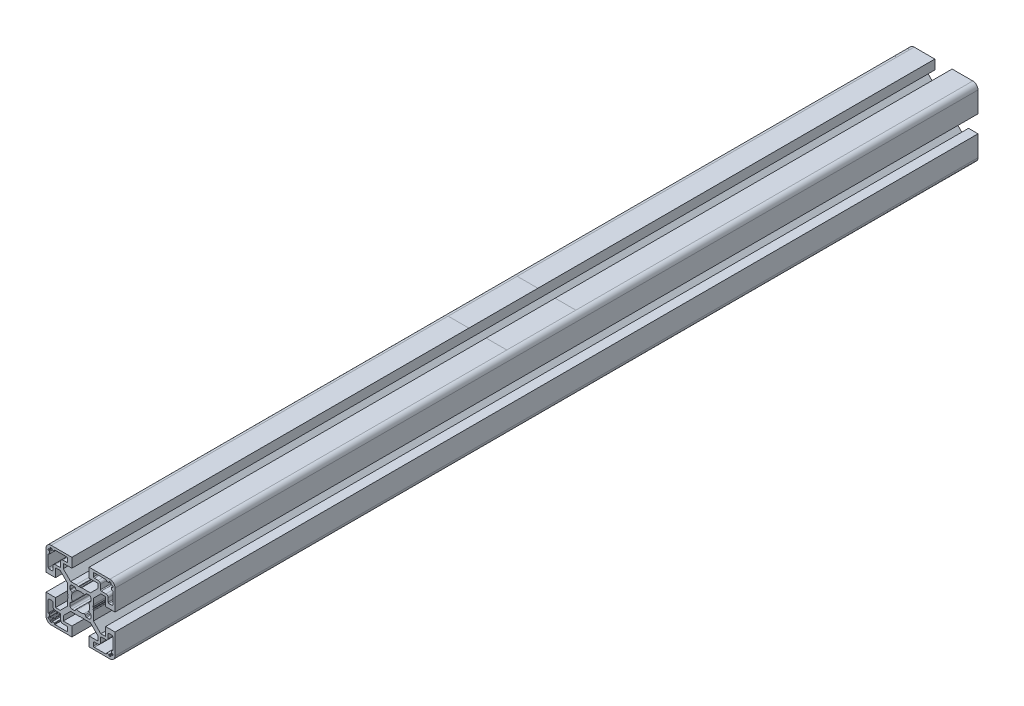
SolidWorks part; units mm, degrees
material "6063-T5"
ref_plane "Front Plane" through (0, 0, 0) normal (0, 0, 1) x (1, 0, 0)
ref_plane "Top Plane" through (0, 0, 0) normal (0, 1, 0) x (1, 0, 0)
ref_plane "Right Plane" through (0, 0, 0) normal (1, 0, 0) x (0, 0, -1)
ref_plane "Plan1" through (0, 0, 50) normal (0, 0, 1) x (1, 0, 0)
sketch "Esquisse1" plane through (0, 0, 50) normal (0, 0, 1) x (1, 0, 0)
  line L0 (-11.2645, -4.6769) -> (-11.2645, 2.1231)
  line L1 (-10.7645, 2.6231) -> (-9.0645, 2.6231)
  line L2 (-8.5645, 2.1231) -> (-8.5645, -0.0769)
  line L3 (-7.2645, -1.3769) -> (-4.5645, -1.3769)
  line L4 (-4.0645, -1.8769) -> (-4.0645, -4.5769)
  line L5 (-2.7645, -5.8769) -> (-0.5645, -5.8769)
  line L6 (-0.0645, -6.3769) -> (-0.0645, -8.0769)
  line L7 (-0.5645, -8.5769) -> (-7.3645, -8.5769)
  line L8 (-7.5645, -8.3769) -> (-7.5645, -8.0769)
  line L9 (-7.7645, -7.8769) -> (-8.9645, -7.8769)
  line L10 (-9.1645, -8.0769) -> (-9.1645, -8.3769)
  line L11 (-9.3645, -8.5769) -> (-9.8645, -8.5769)
  line L12 (-10.1645, -8.2769) -> (-10.1645, -7.7769)
  line L13 (-10.4645, -7.4769) -> (-10.9645, -7.4769)
  line L14 (-11.2645, -7.1769) -> (-11.2645, -6.6769)
  line L15 (-11.0645, -6.4769) -> (-10.7645, -6.4769)
  line L16 (-10.5645, -6.2769) -> (-10.5645, -5.0769)
  line L17 (-10.7645, -4.8769) -> (-11.0645, -4.8769)
  line L18 (14.9355, -8.0769) -> (14.9355, -6.3769)
  line L19 (15.4355, -5.8769) -> (17.6355, -5.8769)
  line L20 (18.9355, -4.5769) -> (18.9355, -1.8769)
  line L21 (19.4355, -1.3769) -> (22.1355, -1.3769)
  line L22 (23.4355, -0.0769) -> (23.4355, 2.1231)
  line L23 (23.9355, 2.6231) -> (25.6355, 2.6231)
  line L24 (26.1355, 2.1231) -> (26.1355, -4.6769)
  line L25 (25.9355, -4.8769) -> (25.6355, -4.8769)
  line L26 (25.4355, -5.0769) -> (25.4355, -6.2769)
  line L27 (25.6355, -6.4769) -> (25.9355, -6.4769)
  line L28 (26.1355, -6.6769) -> (26.1355, -7.1769)
  line L29 (25.8355, -7.4769) -> (25.3355, -7.4769)
  line L30 (25.0355, -7.7769) -> (25.0355, -8.2769)
  line L31 (24.7355, -8.5769) -> (24.2355, -8.5769)
  line L32 (24.0355, -8.3769) -> (24.0355, -8.0769)
  line L33 (23.8355, -7.8769) -> (22.6355, -7.8769)
  line L34 (22.4355, -8.0769) -> (22.4355, -8.3769)
  line L35 (22.2355, -8.5769) -> (15.4355, -8.5769)
  line L36 (-12.5645, 27.1231) -> (-12.5645, 15.1231)
  line L37 (-12.5645, 15.1231) -> (-7.0645, 15.1231)
  line L38 (-7.0645, 15.1231) -> (-7.0645, 20.1231)
  line L39 (-7.0645, 20.1231) -> (-4.3322, 20.1231)
  line L40 (-4.3322, 20.1231) -> (-0.0645, 15.8553)
  line L41 (-0.0645, 15.8553) -> (-0.0645, 10.7767)
  line L42 (0.0025, 10.5267) -> (0.2355, 10.1231)
  line L43 (0.2355, 10.1231) -> (0.0025, 9.7195)
  line L44 (0.0025, 9.2195) -> (0.1846, 8.9042)
  line L45 (0.1846, 8.9042) -> (-0.0645, 7.6231)
  line L46 (-0.0645, 7.6231) -> (-0.0645, 4.3908)
  line L47 (-0.0645, 4.3908) -> (-4.3322, 0.1231)
  line L48 (-4.3322, 0.1231) -> (-7.0645, 0.1231)
  line L49 (-7.0645, 0.1231) -> (-7.0645, 5.1231)
  line L50 (-7.0645, 5.1231) -> (-12.5645, 5.1231)
  line L51 (-12.5645, 5.1231) -> (-12.5645, -6.8769)
  line L52 (-9.5645, -9.8769) -> (2.4355, -9.8769)
  line L53 (2.4355, -9.8769) -> (2.4355, -4.3769)
  line L54 (2.4355, -4.3769) -> (-2.5645, -4.3769)
  line L55 (-2.5645, -4.3769) -> (-2.5645, -1.6447)
  line L56 (-2.5645, -1.6447) -> (1.7033, 2.6231)
  line L57 (1.7033, 2.6231) -> (6.7819, 2.6231)
  line L58 (7.0319, 2.6901) -> (7.4355, 2.9231)
  line L59 (7.4355, 2.9231) -> (7.8391, 2.6901)
  line L60 (8.3391, 2.6901) -> (8.6544, 2.8721)
  line L61 (8.6544, 2.8721) -> (9.9355, 2.6231)
  line L62 (9.9355, 2.6231) -> (13.1678, 2.6231)
  line L63 (13.1678, 2.6231) -> (17.4355, -1.6447)
  line L64 (17.4355, -1.6447) -> (17.4355, -4.3769)
  line L65 (17.4355, -4.3769) -> (12.4355, -4.3769)
  line L66 (12.4355, -4.3769) -> (12.4355, -9.8769)
  line L67 (12.4355, -9.8769) -> (24.4355, -9.8769)
  line L68 (27.4355, -6.8769) -> (27.4355, 5.1231)
  line L69 (27.4355, 5.1231) -> (21.9355, 5.1231)
  line L70 (21.9355, 5.1231) -> (21.9355, 0.1231)
  line L71 (21.9355, 0.1231) -> (19.2033, 0.1231)
  line L72 (19.2033, 0.1231) -> (14.9355, 4.3908)
  line L73 (14.9355, 4.3908) -> (14.9355, 9.4695)
  line L74 (14.8686, 9.7195) -> (14.6355, 10.1231)
  line L75 (14.6355, 10.1231) -> (14.8686, 10.5267)
  line L76 (14.8686, 11.0267) -> (14.6865, 11.342)
  line L77 (14.6865, 11.342) -> (14.9355, 12.6231)
  line L78 (14.9355, 12.6231) -> (14.9355, 15.8553)
  line L79 (14.9355, 15.8553) -> (19.2033, 20.1231)
  line L80 (19.2033, 20.1231) -> (21.9355, 20.1231)
  line L81 (21.9355, 20.1231) -> (21.9355, 15.1231)
  line L82 (21.9355, 15.1231) -> (27.4355, 15.1231)
  line L83 (27.4355, 15.1231) -> (27.4355, 27.1231)
  line L84 (24.4355, 30.1231) -> (12.4355, 30.1231)
  line L85 (12.4355, 30.1231) -> (12.4355, 24.6231)
  line L86 (12.4355, 24.6231) -> (17.4355, 24.6231)
  line L87 (17.4355, 24.6231) -> (17.4355, 21.8908)
  line L88 (17.4355, 21.8908) -> (13.1678, 17.6231)
  line L89 (13.1678, 17.6231) -> (8.0891, 17.6231)
  line L90 (7.8391, 17.5561) -> (7.4355, 17.3231)
  line L91 (7.4355, 17.3231) -> (7.0319, 17.5561)
  line L92 (6.5319, 17.5561) -> (6.2167, 17.3741)
  line L93 (6.2167, 17.3741) -> (4.9355, 17.6231)
  line L94 (4.9355, 17.6231) -> (1.7033, 17.6231)
  line L95 (1.7033, 17.6231) -> (-2.5645, 21.8908)
  line L96 (-2.5645, 21.8908) -> (-2.5645, 24.6231)
  line L97 (-2.5645, 24.6231) -> (2.4355, 24.6231)
  line L98 (2.4355, 24.6231) -> (2.4355, 30.1231)
  line L99 (2.4355, 30.1231) -> (-9.5645, 30.1231)
  line L100 (14.9355, 26.6231) -> (14.9355, 28.3231)
  line L101 (15.4355, 28.8231) -> (22.2355, 28.8231)
  line L102 (22.4355, 28.6231) -> (22.4355, 28.3231)
  line L103 (22.6355, 28.1231) -> (23.8355, 28.1231)
  line L104 (24.0355, 28.3231) -> (24.0355, 28.6231)
  line L105 (24.2355, 28.8231) -> (24.7355, 28.8231)
  line L106 (25.0355, 28.5231) -> (25.0355, 28.0231)
  line L107 (25.3355, 27.7231) -> (25.8355, 27.7231)
  line L108 (26.1355, 27.4231) -> (26.1355, 26.9231)
  line L109 (25.9355, 26.7231) -> (25.6355, 26.7231)
  line L110 (25.4355, 26.5231) -> (25.4355, 25.3231)
  line L111 (25.6355, 25.1231) -> (25.9355, 25.1231)
  line L112 (26.1355, 24.9231) -> (26.1355, 18.1231)
  line L113 (25.6355, 17.6231) -> (23.9355, 17.6231)
  line L114 (23.4355, 18.1231) -> (23.4355, 20.3231)
  line L115 (22.1355, 21.6231) -> (19.4355, 21.6231)
  line L116 (18.9355, 22.1231) -> (18.9355, 24.8231)
  line L117 (17.6355, 26.1231) -> (15.4355, 26.1231)
  line L118 (-11.2645, 18.1231) -> (-11.2645, 24.9231)
  line L119 (-11.0645, 25.1231) -> (-10.7645, 25.1231)
  line L120 (-10.5645, 25.3231) -> (-10.5645, 26.5231)
  line L121 (-10.7645, 26.7231) -> (-11.0645, 26.7231)
  line L122 (-11.2645, 26.9231) -> (-11.2645, 27.4231)
  line L123 (-10.9645, 27.7231) -> (-10.4645, 27.7231)
  line L124 (-10.1645, 28.0231) -> (-10.1645, 28.5231)
  line L125 (-9.8645, 28.8231) -> (-9.3645, 28.8231)
  line L126 (-9.1645, 28.6231) -> (-9.1645, 28.3231)
  line L127 (-8.9645, 28.1231) -> (-7.7645, 28.1231)
  line L128 (-7.5645, 28.3231) -> (-7.5645, 28.6231)
  line L129 (-7.3645, 28.8231) -> (-0.5645, 28.8231)
  line L130 (-0.0645, 28.3231) -> (-0.0645, 26.6231)
  line L131 (-0.5645, 26.1231) -> (-2.7645, 26.1231)
  line L132 (-4.0645, 24.8231) -> (-4.0645, 22.1231)
  line L133 (-4.5645, 21.6231) -> (-7.2645, 21.6231)
  line L134 (-8.5645, 20.3231) -> (-8.5645, 18.1231)
  line L135 (-9.0645, 17.6231) -> (-10.7645, 17.6231)
  line L136 (10.9262, 16.1231) -> (12.4355, 16.1231)
  line L137 (13.4355, 15.1231) -> (13.4355, 13.6138)
  line L138 (13.1703, 13.1723) -> (12.4933, 12.8123)
  line L139 (12.4933, 7.4338) -> (13.1703, 7.0739)
  line L140 (13.4355, 6.6324) -> (13.4355, 5.1231)
  line L141 (12.4355, 4.1231) -> (10.9262, 4.1231)
  line L142 (10.4848, 4.3883) -> (10.1248, 5.0654)
  line L143 (4.7463, 5.0654) -> (4.3863, 4.3883)
  line L144 (3.9449, 4.1231) -> (2.4355, 4.1231)
  line L145 (1.4355, 5.1231) -> (1.4355, 6.6324)
  line L146 (1.7008, 7.0739) -> (2.3778, 7.4338)
  line L147 (2.3778, 12.8123) -> (1.7008, 13.1723)
  line L148 (1.4355, 13.6138) -> (1.4355, 15.1231)
  line L149 (2.4355, 16.1231) -> (3.9449, 16.1231)
  line L150 (4.3863, 15.8578) -> (4.7463, 15.1808)
  line L151 (10.1248, 15.1808) -> (10.4848, 15.8578)
  arc A0 (-11.2645, 2.1231) -> (-10.7645, 2.6231) centre (-10.7645, 2.1231) cw
  arc A1 (-9.0645, 2.6231) -> (-8.5645, 2.1231) centre (-9.0645, 2.1231) cw
  arc A2 (-8.5645, -0.0769) -> (-7.2645, -1.3769) centre (-7.2645, -0.0769) ccw
  arc A3 (-4.5645, -1.3769) -> (-4.0645, -1.8769) centre (-4.5645, -1.8769) cw
  arc A4 (-4.0645, -4.5769) -> (-2.7645, -5.8769) centre (-2.7645, -4.5769) ccw
  arc A5 (-0.5645, -5.8769) -> (-0.0645, -6.3769) centre (-0.5645, -6.3769) cw
  arc A6 (-0.0645, -8.0769) -> (-0.5645, -8.5769) centre (-0.5645, -8.0769) cw
  arc A7 (-7.3645, -8.5769) -> (-7.5645, -8.3769) centre (-7.3645, -8.3769) cw
  arc A8 (-7.5645, -8.0769) -> (-7.7645, -7.8769) centre (-7.7645, -8.0769) ccw
  arc A9 (-8.9645, -7.8769) -> (-9.1645, -8.0769) centre (-8.9645, -8.0769) ccw
  arc A10 (-9.1645, -8.3769) -> (-9.3645, -8.5769) centre (-9.3645, -8.3769) cw
  arc A11 (-9.8645, -8.5769) -> (-10.1645, -8.2769) centre (-9.8645, -8.2769) cw
  arc A12 (-10.1645, -7.7769) -> (-10.4645, -7.4769) centre (-10.4645, -7.7769) ccw
  arc A13 (-10.9645, -7.4769) -> (-11.2645, -7.1769) centre (-10.9645, -7.1769) cw
  arc A14 (-11.2645, -6.6769) -> (-11.0645, -6.4769) centre (-11.0645, -6.6769) cw
  arc A15 (-10.7645, -6.4769) -> (-10.5645, -6.2769) centre (-10.7645, -6.2769) ccw
  arc A16 (-10.5645, -5.0769) -> (-10.7645, -4.8769) centre (-10.7645, -5.0769) ccw
  arc A17 (-11.0645, -4.8769) -> (-11.2645, -4.6769) centre (-11.0645, -4.6769) cw
  arc A18 (14.9355, -6.3769) -> (15.4355, -5.8769) centre (15.4355, -6.3769) cw
  arc A19 (17.6355, -5.8769) -> (18.9355, -4.5769) centre (17.6355, -4.5769) ccw
  arc A20 (18.9355, -1.8769) -> (19.4355, -1.3769) centre (19.4355, -1.8769) cw
  arc A21 (22.1355, -1.3769) -> (23.4355, -0.0769) centre (22.1355, -0.0769) ccw
  arc A22 (23.4355, 2.1231) -> (23.9355, 2.6231) centre (23.9355, 2.1231) cw
  arc A23 (25.6355, 2.6231) -> (26.1355, 2.1231) centre (25.6355, 2.1231) cw
  arc A24 (26.1355, -4.6769) -> (25.9355, -4.8769) centre (25.9355, -4.6769) cw
  arc A25 (25.6355, -4.8769) -> (25.4355, -5.0769) centre (25.6355, -5.0769) ccw
  arc A26 (25.4355, -6.2769) -> (25.6355, -6.4769) centre (25.6355, -6.2769) ccw
  arc A27 (25.9355, -6.4769) -> (26.1355, -6.6769) centre (25.9355, -6.6769) cw
  arc A28 (26.1355, -7.1769) -> (25.8355, -7.4769) centre (25.8355, -7.1769) cw
  arc A29 (25.3355, -7.4769) -> (25.0355, -7.7769) centre (25.3355, -7.7769) ccw
  arc A30 (25.0355, -8.2769) -> (24.7355, -8.5769) centre (24.7355, -8.2769) cw
  arc A31 (24.2355, -8.5769) -> (24.0355, -8.3769) centre (24.2355, -8.3769) cw
  arc A32 (24.0355, -8.0769) -> (23.8355, -7.8769) centre (23.8355, -8.0769) ccw
  arc A33 (22.6355, -7.8769) -> (22.4355, -8.0769) centre (22.6355, -8.0769) ccw
  arc A34 (22.4355, -8.3769) -> (22.2355, -8.5769) centre (22.2355, -8.3769) cw
  arc A35 (15.4355, -8.5769) -> (14.9355, -8.0769) centre (15.4355, -8.0769) cw
  arc A36 (-9.5645, 30.1231) -> (-12.5645, 27.1231) centre (-9.5645, 27.1231) ccw
  arc A37 (-0.0645, 10.7767) -> (0.0025, 10.5267) centre (0.4355, 10.7767) ccw
  arc A38 (0.0025, 9.7195) -> (0.0025, 9.2195) centre (0.4355, 9.4695) ccw
  arc A39 (-12.5645, -6.8769) -> (-9.5645, -9.8769) centre (-9.5645, -6.8769) ccw
  arc A40 (6.7819, 2.6231) -> (7.0319, 2.6901) centre (6.7819, 3.1231) ccw
  arc A41 (7.8391, 2.6901) -> (8.3391, 2.6901) centre (8.0891, 3.1231) ccw
  arc A42 (24.4355, -9.8769) -> (27.4355, -6.8769) centre (24.4355, -6.8769) ccw
  arc A43 (14.9355, 9.4695) -> (14.8686, 9.7195) centre (14.4355, 9.4695) ccw
  arc A44 (14.8686, 10.5267) -> (14.8686, 11.0267) centre (14.4355, 10.7767) ccw
  arc A45 (27.4355, 27.1231) -> (24.4355, 30.1231) centre (24.4355, 27.1231) ccw
  arc A46 (8.0891, 17.6231) -> (7.8391, 17.5561) centre (8.0891, 17.1231) ccw
  arc A47 (7.0319, 17.5561) -> (6.5319, 17.5561) centre (6.7819, 17.1231) ccw
  arc A48 (14.9355, 28.3231) -> (15.4355, 28.8231) centre (15.4355, 28.3231) cw
  arc A49 (22.2355, 28.8231) -> (22.4355, 28.6231) centre (22.2355, 28.6231) cw
  arc A50 (22.4355, 28.3231) -> (22.6355, 28.1231) centre (22.6355, 28.3231) ccw
  arc A51 (23.8355, 28.1231) -> (24.0355, 28.3231) centre (23.8355, 28.3231) ccw
  arc A52 (24.0355, 28.6231) -> (24.2355, 28.8231) centre (24.2355, 28.6231) cw
  arc A53 (24.7355, 28.8231) -> (25.0355, 28.5231) centre (24.7355, 28.5231) cw
  arc A54 (25.0355, 28.0231) -> (25.3355, 27.7231) centre (25.3355, 28.0231) ccw
  arc A55 (25.8355, 27.7231) -> (26.1355, 27.4231) centre (25.8355, 27.4231) cw
  arc A56 (26.1355, 26.9231) -> (25.9355, 26.7231) centre (25.9355, 26.9231) cw
  arc A57 (25.6355, 26.7231) -> (25.4355, 26.5231) centre (25.6355, 26.5231) ccw
  arc A58 (25.4355, 25.3231) -> (25.6355, 25.1231) centre (25.6355, 25.3231) ccw
  arc A59 (25.9355, 25.1231) -> (26.1355, 24.9231) centre (25.9355, 24.9231) cw
  arc A60 (26.1355, 18.1231) -> (25.6355, 17.6231) centre (25.6355, 18.1231) cw
  arc A61 (23.9355, 17.6231) -> (23.4355, 18.1231) centre (23.9355, 18.1231) cw
  arc A62 (23.4355, 20.3231) -> (22.1355, 21.6231) centre (22.1355, 20.3231) ccw
  arc A63 (19.4355, 21.6231) -> (18.9355, 22.1231) centre (19.4355, 22.1231) cw
  arc A64 (18.9355, 24.8231) -> (17.6355, 26.1231) centre (17.6355, 24.8231) ccw
  arc A65 (15.4355, 26.1231) -> (14.9355, 26.6231) centre (15.4355, 26.6231) cw
  arc A66 (-11.2645, 24.9231) -> (-11.0645, 25.1231) centre (-11.0645, 24.9231) cw
  arc A67 (-10.7645, 25.1231) -> (-10.5645, 25.3231) centre (-10.7645, 25.3231) ccw
  arc A68 (-10.5645, 26.5231) -> (-10.7645, 26.7231) centre (-10.7645, 26.5231) ccw
  arc A69 (-11.0645, 26.7231) -> (-11.2645, 26.9231) centre (-11.0645, 26.9231) cw
  arc A70 (-11.2645, 27.4231) -> (-10.9645, 27.7231) centre (-10.9645, 27.4231) cw
  arc A71 (-10.4645, 27.7231) -> (-10.1645, 28.0231) centre (-10.4645, 28.0231) ccw
  arc A72 (-10.1645, 28.5231) -> (-9.8645, 28.8231) centre (-9.8645, 28.5231) cw
  arc A73 (-9.3645, 28.8231) -> (-9.1645, 28.6231) centre (-9.3645, 28.6231) cw
  arc A74 (-9.1645, 28.3231) -> (-8.9645, 28.1231) centre (-8.9645, 28.3231) ccw
  arc A75 (-7.7645, 28.1231) -> (-7.5645, 28.3231) centre (-7.7645, 28.3231) ccw
  arc A76 (-7.5645, 28.6231) -> (-7.3645, 28.8231) centre (-7.3645, 28.6231) cw
  arc A77 (-0.5645, 28.8231) -> (-0.0645, 28.3231) centre (-0.5645, 28.3231) cw
  arc A78 (-0.0645, 26.6231) -> (-0.5645, 26.1231) centre (-0.5645, 26.6231) cw
  arc A79 (-2.7645, 26.1231) -> (-4.0645, 24.8231) centre (-2.7645, 24.8231) ccw
  arc A80 (-4.0645, 22.1231) -> (-4.5645, 21.6231) centre (-4.5645, 22.1231) cw
  arc A81 (-7.2645, 21.6231) -> (-8.5645, 20.3231) centre (-7.2645, 20.3231) ccw
  arc A82 (-8.5645, 18.1231) -> (-9.0645, 17.6231) centre (-9.0645, 18.1231) cw
  arc A83 (-10.7645, 17.6231) -> (-11.2645, 18.1231) centre (-10.7645, 18.1231) cw
  arc A84 (12.4355, 16.1231) -> (13.4355, 15.1231) centre (12.4355, 15.1231) cw
  arc A85 (13.4355, 13.6138) -> (13.1703, 13.1723) centre (12.9355, 13.6138) cw
  arc A86 (12.4933, 12.8123) -> (12.2678, 12.1754) centre (12.728, 12.3708) ccw
  arc A87 (12.2678, 12.1754) -> (12.2678, 8.0708) centre (7.4355, 10.1231) cw
  arc A88 (12.2678, 8.0708) -> (12.4933, 7.4338) centre (12.728, 7.8753) ccw
  arc A89 (13.1703, 7.0739) -> (13.4355, 6.6324) centre (12.9355, 6.6324) cw
  arc A90 (13.4355, 5.1231) -> (12.4355, 4.1231) centre (12.4355, 5.1231) cw
  arc A91 (10.9262, 4.1231) -> (10.4848, 4.3883) centre (10.9262, 4.6231) cw
  arc A92 (10.1248, 5.0654) -> (9.4878, 5.2908) centre (9.6833, 4.8306) ccw
  arc A93 (9.4878, 5.2908) -> (5.3832, 5.2908) centre (7.4355, 10.1231) cw
  arc A94 (5.3832, 5.2908) -> (4.7463, 5.0654) centre (5.1878, 4.8306) ccw
  arc A95 (4.3863, 4.3883) -> (3.9449, 4.1231) centre (3.9449, 4.6231) cw
  arc A96 (2.4355, 4.1231) -> (1.4355, 5.1231) centre (2.4355, 5.1231) cw
  arc A97 (1.4355, 6.6324) -> (1.7008, 7.0739) centre (1.9355, 6.6324) cw
  arc A98 (2.3778, 7.4338) -> (2.6033, 8.0708) centre (2.1431, 7.8753) ccw
  arc A99 (2.6033, 8.0708) -> (2.6033, 12.1754) centre (7.4355, 10.1231) cw
  arc A100 (2.6033, 12.1754) -> (2.3778, 12.8123) centre (2.1431, 12.3708) ccw
  arc A101 (1.7008, 13.1723) -> (1.4355, 13.6138) centre (1.9355, 13.6138) cw
  arc A102 (1.4355, 15.1231) -> (2.4355, 16.1231) centre (2.4355, 15.1231) cw
  arc A103 (3.9449, 16.1231) -> (4.3863, 15.8578) centre (3.9449, 15.6231) cw
  arc A104 (4.7463, 15.1808) -> (5.3832, 14.9553) centre (5.1878, 15.4155) ccw
  arc A105 (5.3832, 14.9553) -> (9.4878, 14.9553) centre (7.4355, 10.1231) cw
  arc A106 (9.4878, 14.9553) -> (10.1248, 15.1808) centre (9.6833, 15.4155) ccw
  arc A107 (10.4848, 15.8578) -> (10.9262, 16.1231) centre (10.9262, 15.6231) cw
extrude "Boss.-Extru.1" add sketch "Esquisse1" against normal blind 500
sketch "Esquisse2" plane through (0, 30.1231, 0) normal (0, 1, 0) x (1, 0, 0)
  line L0 (-12.5645, 450) -> (-12.5645, -50) construction
  line L1 (-12.5645, 220) -> (27.4355, 220)
  line L2 (-12.5645, 220) -> (-12.5645, 180)
  line L3 (-12.5645, 180) -> (27.4355, 180)
  line L4 (27.4355, 220) -> (27.4355, 180)
  line L5 (27.4355, 450) -> (27.4355, -50) construction
  line L6 (-12.5645, 200) -> (27.4355, 200) construction
  dimension "D1" = 40
split line "Ligne de séparation1"
